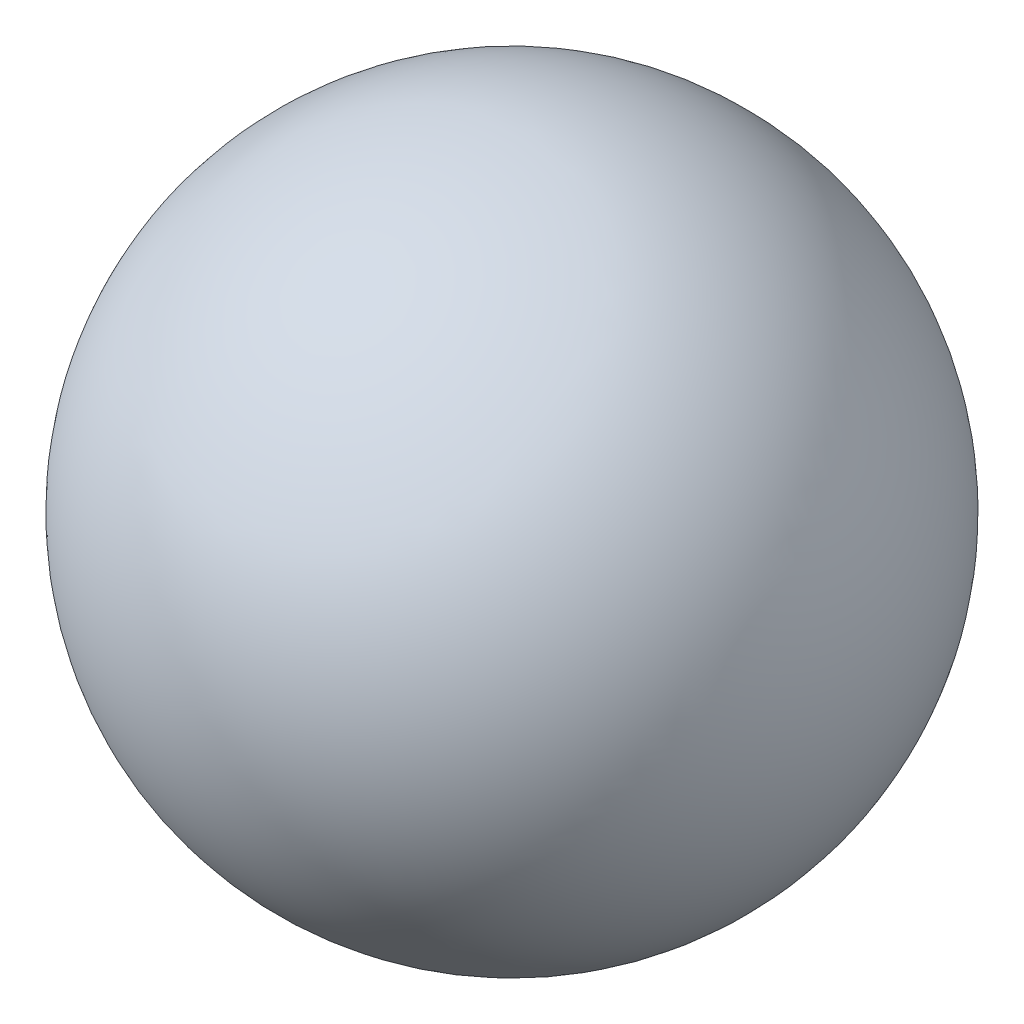
SolidWorks part; units mm, degrees
ref_plane "Front Plane" through (0, 0, 0) normal (0, 0, 1) x (1, 0, 0)
ref_plane "Top Plane" through (0, 0, 0) normal (0, 1, 0) x (1, 0, 0)
ref_plane "Right Plane" through (0, 0, 0) normal (1, 0, 0) x (0, 0, -1)
sketch "Sketch1" plane through (0, 0, 0) normal (0, 0, 1) x (1, 0, 0)
  line L0 (0, 0) -> (300, 0) construction
  line L1 (0, 0) -> (300, 0)
  arc A0 (0, 0) -> (300, 0) centre (150, 0) cw
  point P3 (0, 0)
  dimension "D1" = 150
revolve "Revolve1" add sketch "Sketch1" angle 360 about L0
